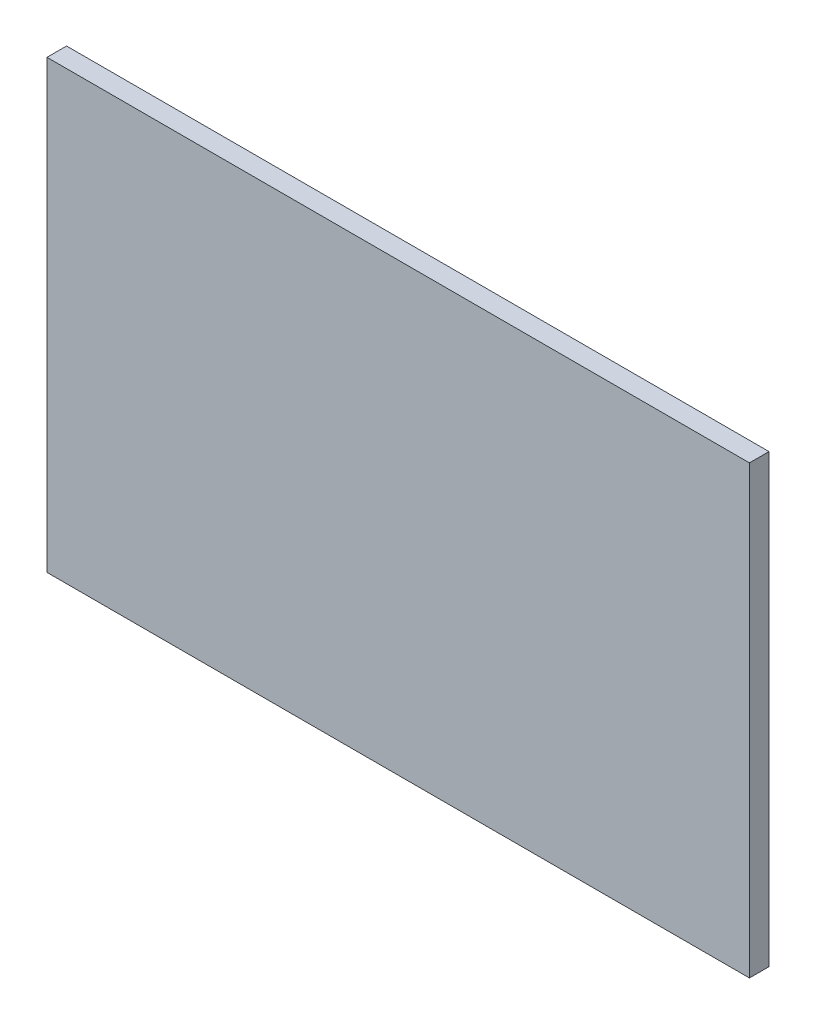
SolidWorks part; units mm, degrees
material "Custom Plastic"
ref_plane "Front Plane" through (0, 0, 0) normal (0, 0, 1) x (1, 0, 0)
ref_plane "Top Plane" through (0, 0, 0) normal (0, 1, 0) x (1, 0, 0)
ref_plane "Right Plane" through (0, 0, 0) normal (1, 0, 0) x (0, 0, -1)
sketch "Sketch1" plane through (0, 0, 0) normal (0, 0, 1) x (1, 0, 0)
  line L1 (-179.5, -114) -> (179.5, -114)
  line L2 (-179.5, -114) -> (-179.5, 114)
  line L3 (-179.5, 114) -> (179.5, 114)
  line L4 (179.5, -114) -> (179.5, 114)
  line L5 (-179.5, -114) -> (179.5, 114) construction
  line L6 (-179.5, 114) -> (179.5, -114) construction
  point P0 (0, 0)
extrude "Boss-Extrude1" add sketch "Sketch1" along normal blind 10
